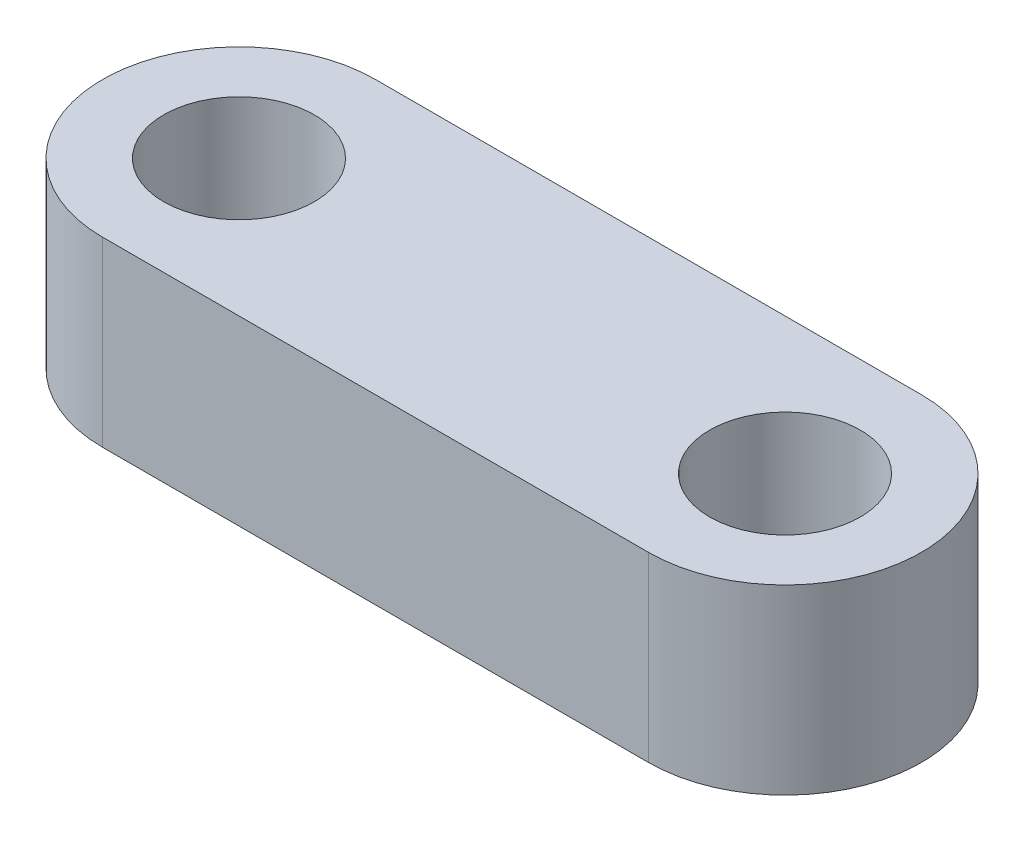
SolidWorks part; units mm, degrees
material "ABS"
ref_plane "Front Plane" through (0, 0, 0) normal (0, 0, 1) x (1, 0, 0)
ref_plane "Top Plane" through (0, 0, 0) normal (0, 1, 0) x (1, 0, 0)
ref_plane "Right Plane" through (0, 0, 0) normal (1, 0, 0) x (0, 0, -1)
sketch "Sketch1" plane through (0, 0, 0) normal (0, 1, 0) x (1, 0, 0)
  line L0 (0, 0) -> (19.05, 0) construction
  line L1 (0, 4.7625) -> (19.05, 4.7625)
  line L2 (0, -4.7625) -> (19.05, -4.7625)
  circle A0 centre (0, 0) radius 2.6289
  circle A1 centre (19.05, 0) radius 2.6289
  arc A2 (0, 4.7625) -> (0, -4.7625) centre (0, 0) ccw
  arc A3 (19.05, 4.7625) -> (19.05, -4.7625) centre (19.05, 0) cw
  dimension "D1" = 5.2578
  dimension "D2" = 5.2578
  dimension "D4" = 4.7625
  dimension "D3" = 19.05
extrude "Boss-Extrude1" add sketch "Sketch1" along normal blind 6.35
